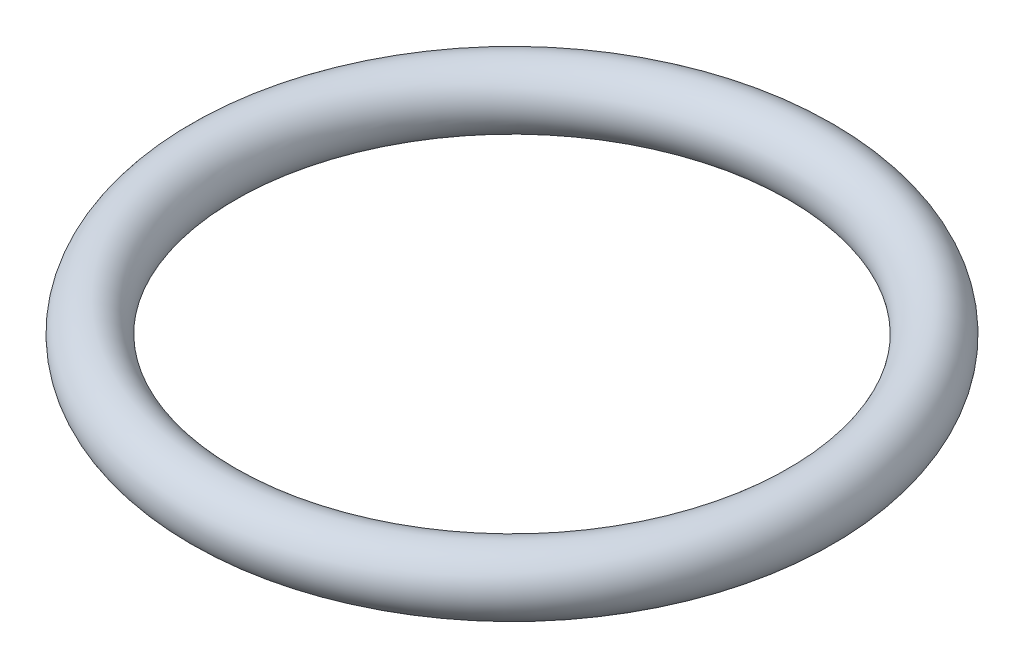
SolidWorks part; units mm, degrees
material "BUTYL"
ref_plane "Front Plane" through (0, 0, 0) normal (0, 0, 1) x (1, 0, 0)
ref_plane "Top Plane" through (0, 0, 0) normal (0, 1, 0) x (1, 0, 0)
ref_plane "Right Plane" through (0, 0, 0) normal (1, 0, 0) x (0, 0, -1)
sketch "Sketch1" plane through (0, 0, 0) normal (0, 0, 1) x (1, 0, 0)
  line L0 (0, 0) -> (0, 10.4404) construction
  circle A0 centre (9.525, 0) radius 0.9906
  dimension "D2" = 1.9812
  dimension "D1" = 19.05
revolve "Revolve1" add sketch "Sketch1" angle 360 about L0
